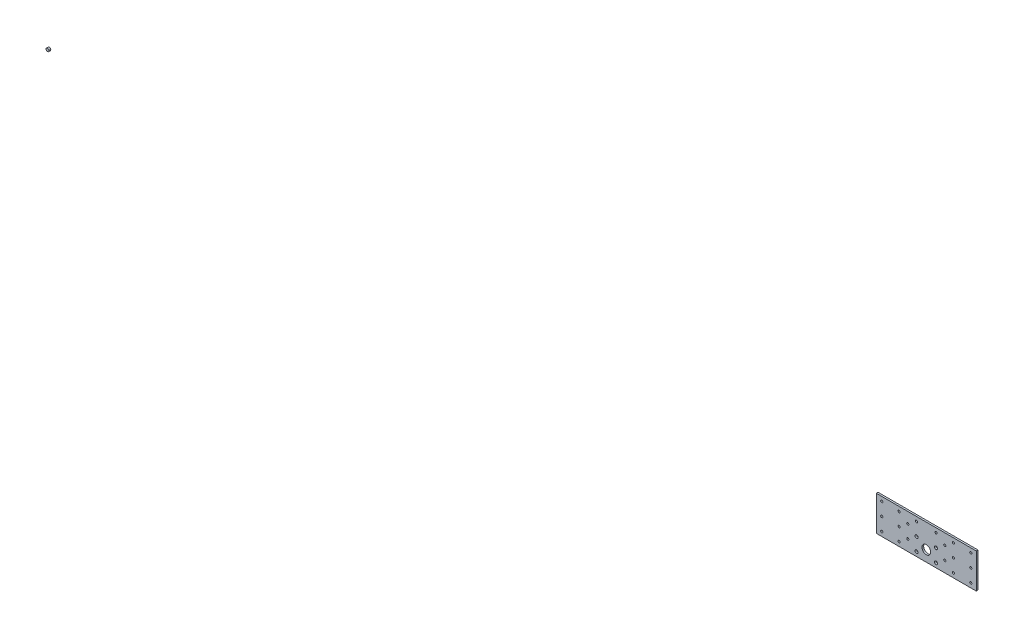
SolidWorks part; units mm, degrees
ref_plane "Plan de face" through (0, 0, 0) normal (0, 0, 1) x (1, 0, 0)
ref_plane "Plan de dessus" through (0, 0, 0) normal (0, 1, 0) x (1, 0, 0)
ref_plane "Plan de droite" through (0, 0, 0) normal (1, 0, 0) x (0, 0, -1)
sketch "Esquisse1" plane through (0, 0, 0) normal (0, 0, 1) x (1, 0, 0)
  line L0 (2.5, 16) -> (2.5, 0) construction
  line L1 (23, 0) -> (0, 0)
  line L3 (46, 16) -> (0, 16)
  line L4 (0, 0) -> (0, 16)
  line L5 (10.5, 16) -> (10.5, 0) construction
  line L6 (10.5, 0) -> (11.5, 0) construction
  line L7 (14.5, 16) -> (14.5, 0) construction
  line L8 (18.5, 16) -> (18.5, 0) construction
  line L9 (0, 2) -> (46, 2) construction
  line L10 (0, 8) -> (46, 8) construction
  line L11 (46, 14) -> (0, 14) construction
  line L12 (23, 0) -> (46, 0)
  line L13 (27.5, 16) -> (27.5, 0) construction
  line L14 (31.5, 16) -> (31.5, 0) construction
  line L15 (35.5, 0) -> (34.5, 0) construction
  line L16 (35.5, 16) -> (35.5, 0) construction
  line L17 (43.5, 16) -> (43.5, 0) construction
  line L18 (46, 0) -> (46, 16)
  circle A0 centre (2.5, 8) radius 0.5
  circle A1 centre (2.5, 14) radius 0.5
  circle A2 centre (2.5, 2) radius 0.5
  circle A3 centre (10.5, 8) radius 0.5
  circle A4 centre (10.5, 2) radius 0.5
  circle A5 centre (10.5, 14) radius 0.5
  circle A7 centre (23, 5) radius 2
  circle A8 centre (18.5, 14) radius 0.5
  circle A9 centre (-381.5, 2) radius 0.7
  circle A10 centre (14.5, 5) radius 0.5
  circle A11 centre (14.5, 11) radius 0.5
  circle A12 centre (18.5, 2) radius 0.7
  circle A13 centre (18.5, 8) radius 0.7
  circle A14 centre (27.5, 2) radius 0.7
  circle A15 centre (31.5, 11) radius 0.5
  circle A16 centre (31.5, 5) radius 0.5
  circle A17 centre (27.5, 14) radius 0.5
  circle A18 centre (35.5, 14) radius 0.5
  circle A19 centre (35.5, 2) radius 0.5
  circle A20 centre (35.5, 8) radius 0.5
  circle A21 centre (43.5, 2) radius 0.5
  circle A22 centre (43.5, 14) radius 0.5
  circle A23 centre (43.5, 8) radius 0.5
  circle A24 centre (27.5, 8) radius 0.7
  point P2 (0, 0)
  point P46 (0, 0)
  point P48 (23, 14)
  point P49 (23, 8)
  point P50 (23, 2)
  point P82 (0, 0)
  point P83 (0, 0)
  point P84 (0, 0)
extrude "Boss.-Extru.1" add sketch "Esquisse1" along normal blind 0.8
